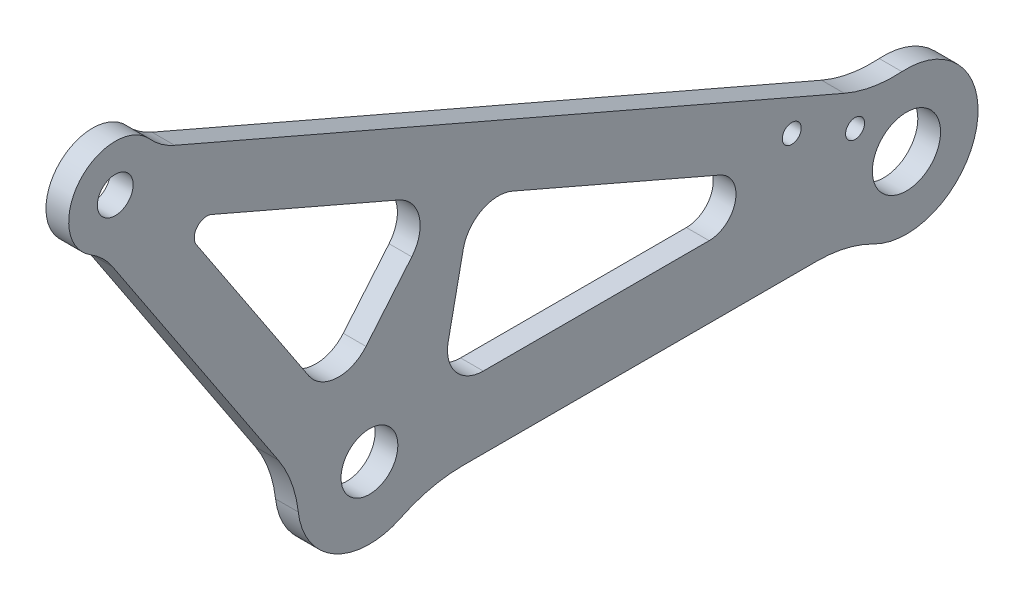
SolidWorks part; units mm, degrees
material "AISI 1020"
ref_plane "Front Plane" through (0, 0, 0) normal (0, 0, 1) x (1, 0, 0)
ref_plane "Top Plane" through (0, 0, 0) normal (0, 1, 0) x (1, 0, 0)
ref_plane "Right Plane" through (0, 0, 0) normal (1, 0, 0) x (0, 0, -1)
sketch "Sketch1" plane through (0, 0, 0) normal (1, 0, 0) x (0, 0, -1)
  line L0 (-60.7171, 0) -> (60.7171, 0)
  line L3 (0, -143.7223) -> (0, 143.7223) construction
  line L4 (-149.7529, 101.5535) -> (-94.5581, 18.1812)
  line L5 (-134.4049, 119.8783) -> (67.4524, 32.5212)
  line L6 (-75, 14) -> (75, 14) construction
  line L8 (-146, 114) -> (-75, 14) construction
  arc A20 (-134.4049, 119.8783) -> (-149.7529, 101.5535) centre (-146, 114) ccw
  arc A22 (-94.5581, 18.1812) -> (-60.7171, 0) centre (-75, 14) ccw
  arc A23 (60.7171, 0) -> (67.4524, 32.5212) centre (75, 14) ccw
  point P5 (0, 0)
  point P14 (0, 0)
  dimension "D3" = 20
  dimension "D5" = 13
  dimension "D6" = 20
  dimension "D4" = 127
  dimension "D7" = 254
  dimension "D10" = 6
  dimension "D11" = 6
  dimension "D9" = 3
  dimension "D12" = 3
  dimension "D13" = 6
  dimension "D14" = 6
  dimension "D2" = 150
  dimension "D8" = 122.6418
extrude "Boss-Extrude1" add sketch "Sketch1" along normal blind 6.35
hole_wizard "3/4 (0.75) Diameter Hole1" positions "Sketch4" profile "Sketch3" hole size "3/4" standard "ANSI Inch" end condition up to next
sketch "Sketch4" plane through (6.35, 0, 0) normal (1, 0, 0) x (0, 0, -1)
  point P5 (75, 14)
sketch "Sketch3" plane through (6.35, 14, -75) normal (0, 1, 0) x (0, 0, -1)
  line L0 (0, 0) -> (0, 6.35)
  line L1 (0, 6.35) -> (9.525, 6.35)
  line L2 (9.525, 6.35) -> (9.525, 0)
  line L5 (9.525, 0) -> (0, 0)
  line L11 (0, -6.35) -> (0, 107.95) construction
  dimension "Thru Hole Dia." = 19.05
  dimension "Thru Hole Depth" = 6.35
hole_wizard "Ø10.0 (10) Diameter Hole1" positions "Sketch9" profile "Sketch6" hole size "Ø10.0" standard "ANSI Metric" end condition up to next
sketch "Sketch9" plane through (6.35, 0, 0) normal (1, 0, 0) x (0, 0, -1)
  point P0 (-146, 114)
sketch "Sketch6" plane through (6.35, 114, 146) normal (0, 1, 0) x (0, 0, -1)
  line L0 (0, 0) -> (0, 6.35)
  line L1 (0, 6.35) -> (5, 6.35)
  line L2 (5, 6.35) -> (5, 0)
  line L5 (5, 0) -> (0, 0)
  line L11 (0, -6.35) -> (0, 107.95) construction
  dimension "Thru Hole Dia." = 10
  dimension "Thru Hole Depth" = 6.35
hole_wizard "Ø5/8\" Diameter Hole2" positions "Sketch16" profile "Sketch11" hole size "5/8" standard "ANSI Inch" end condition up to next
sketch "Sketch16" plane through (6.35, 0, 0) normal (1, 0, 0) x (0, 0, -1)
  line L0 (75, 14) -> (157.5513, 156.983)
  line L2 (0, 0) -> (0, 108.153) construction
  line L4 (-146, 114) -> (-119.4521, 194.8786)
  line L6 (-174.545, 70.324) -> (-178.0536, 59.6351) construction
  line L7 (-174.545, 70.324) -> (-178.0536, 59.6351) construction
  arc A0 (-94.5581, 18.1812) -> (-60.7171, 0) centre (-75, 14) ccw construction
  point P0 (-75, 14)
  dimension "D1" = 30
sketch "Sketch11" plane through (6.35, 14, 75) normal (0, 1, 0) x (0, 0, -1)
  line L0 (0, 0) -> (0, 6.35)
  line L1 (0, 6.35) -> (7.9375, 6.35)
  line L2 (7.9375, 6.35) -> (7.9375, 0)
  line L5 (7.9375, 0) -> (0, 0)
  line L11 (0, -6.35) -> (0, 107.95) construction
  dimension "Thru Hole Dia." = 15.875
  dimension "Thru Hole Depth" = 6.35
sketch "Sketch8" plane through (6.35, 0, 0) normal (1, 0, 0) x (0, 0, -1)
  line L2 (-54.5605, 67.8903) -> (-46.3008, 64.3157) construction
  line L3 (-52.9877, 32.028) -> (-48.7918, 52.2877)
  line L7 (-75.9573, 42.3434) -> (-63.1664, 57.6152)
  line L9 (-123.3455, 90.6494) -> (-91.9619, 43.2441)
  line L10 (-119.037, 95.7935) -> (-66.861, 73.2135)
  line L11 (19.8861, 20) -> (-43.1955, 20)
  line L12 (67.4524, 32.5212) -> (-134.4049, 119.8783) construction
  line L13 (-149.7529, 101.5535) -> (-94.5581, 18.1812) construction
  line L14 (-60.7171, 0) -> (60.7171, 0) construction
  line L15 (-84.5632, 32.0683) -> (-84.2827, 31.6447) construction
  line L16 (-55.4787, 20) -> (-55.9867, 20) construction
  line L17 (-54.5605, 67.8903) -> (-46.3008, 64.3157) construction
  line L18 (-35.0279, 59.4372) -> (22.8649, 34.3831)
  line L19 (-120.4271, 92.5814) -> (-104.3957, 79.1543) construction
  line L20 (19.8861, 27.5) -> (27.9693, 25.826) construction
  line L21 (-29.8567, 10) -> (10.3311, 10) construction
  arc A0 (-52.9877, 32.028) -> (-43.1955, 20) centre (-43.1955, 30) ccw
  arc A2 (-48.7918, 52.2877) -> (-35.0279, 59.4372) centre (-38.9996, 50.2597) cw
  arc A4 (-63.1664, 57.6152) -> (-66.861, 73.2135) centre (-70.8327, 64.0361) ccw
  arc A14 (-119.037, 95.7935) -> (-123.3455, 90.6494) centre (-120.4271, 92.5814) ccw
  arc A20 (-75.9573, 42.3434) -> (-91.9619, 43.2441) centre (-83.6236, 48.7643) cw
  arc A25 (-134.4049, 119.8783) -> (-149.7529, 101.5535) centre (-146, 114) ccw construction
  circle A27 centre (-146, 114) radius 5 construction
  arc A36 (-94.5581, 18.1812) -> (-60.7171, 0) centre (-75, 14) ccw construction
  circle A39 centre (-75, 14) radius 7.9375 construction
  arc A40 (19.8861, 20) -> (22.8649, 34.3831) centre (19.8861, 27.5) ccw
  circle A54 centre (-75, 14) radius 19.9375
  arc A55 (-55.9867, 20) -> (-84.2827, 31.6447) centre (-75, 14) ccw construction
  point P7 (-33.5049, 66.1162)
  point P19 (-33.4763, 76.1997)
  dimension "D8" = 8
  dimension "D9" = 12.0625
  dimension "D11" = 9
  dimension "D7" = 4
  dimension "D1" = 7
  dimension "D10" = 24.8576
  dimension "D2" = 15
  dimension "D12" = 10
  dimension "D13" = 14.6862
  dimension "D3" = 12
  dimension "D5" = 16
  dimension "D6" = 20
  dimension "D4" = 16
extrude "Cut-Extrude1" cut sketch "Sketch8" against normal up to next
fillet "Fillet1" radius 35 1 edges at (3.175, 18.1812, 94.5581)
fillet "Fillet3" radius 35 2 edges at (3.175, 32.5212, -67.4524) (3.175, 0, -60.7171)
fillet "Fillet4" radius 20 2 edges at (3.175, 101.5535, 149.7529) (3.175, 119.8783, 134.4049)
fillet "Fillet6" radius 40 1 edges at (3.175, 0, 60.7171)
sketch "Sketch17" [suppressed] plane through (0, 0, 0) normal (-1, 0, 0) x (0, 0, 1)
  line L0 (-31.692, 47.9971) -> (-74.6306, 61.6169)
  line L1 (-57.6351, 36.7697) -> (129.4114, 117.7173) construction
  line L2 (-134.8033, 70.2122) -> (-137.856, 60.5882)
  line L3 (-135.7084, 50.8215) -> (-89.7688, 0.5136)
  line L4 (-57.6351, 36.7697) -> (-31.692, 47.9971)
  line L6 (-84.0792, 16.8799) -> (-65.9208, 11.1201) construction
  line L7 (-100.5678, 75.614) -> (-71.9719, 66.5436) construction
  line L8 (-77.8799, 4.9208) -> (-72.1201, 23.0792) construction
  line L9 (-74.6306, 61.6169) -> (-101.2349, 70.0556) construction
  line L10 (-101.2349, 70.0556) -> (-122.2479, 76.7207)
  arc A0 (-73.7404, 33.9603) -> (-65.9164, -3.8182) centre (-75, 14) ccw construction
  arc A1 (-73.7404, 33.9603) -> (-57.6351, 36.7697) centre (-71.5361, 68.8908) ccw construction
  arc A2 (-73.7404, 33.9603) -> (-89.7688, 0.5136) centre (-75, 14) ccw
  arc A3 (-73.7404, 33.9603) -> (-57.6351, 36.7697) centre (-71.5361, 68.8908) ccw
  arc A4 (-137.856, 60.5882) -> (-135.7084, 50.8215) centre (-128.324, 57.5647) ccw
  arc A5 (-122.2479, 76.7207) -> (-134.8033, 70.2122) centre (-125.2713, 67.1887) ccw
  arc A6 (-101.2349, 70.0556) -> (-74.6306, 61.6169) centre (-86.2698, 71.0788) ccw
  circle A7 centre (-75, 14) radius 9.525 construction
  arc A8 (-71.9719, 66.5436) -> (-100.5678, 75.614) centre (-86.2698, 71.0788) ccw construction
  arc A9 (-100.5678, 75.614) -> (-101.2349, 70.0556) centre (-86.2698, 71.0788) ccw construction
  arc A10 (-74.6306, 61.6169) -> (-71.9719, 66.5436) centre (-86.2698, 71.0788) ccw construction
  point P15 (-75, 14)
  point P18 (-86.2698, 71.0788)
  point P26 (-139.6016, 55.0849)
  point P29 (-131.7798, 79.7442)
  point P31 (-75, 14)
  dimension "D5" = 10
  dimension "D1" = 41
  dimension "D2" = 45.5
  dimension "D3" = 120
  dimension "D4" = 74
  dimension "D6" = 30
  dimension "D7" = 51
  dimension "D8" = 28
extrude "Boss-Extrude2" [suppressed] add sketch "Sketch17" against normal up to surface (6.35 mm away)
hole_wizard "M5 Clearance Hole1" positions "Sketch21" profile "Sketch19" hole size "M5" standard "ANSI Metric"
sketch "Sketch21" [suppressed] plane through (0, 0, 0) normal (-1, 0, 0) x (0, 0, 1)
  line L0 (-125.2509, 66.6577) -> (-73.9498, 50.3854) construction
  line L2 (-31.692, 47.9971) -> (-74.6306, 61.6169) construction
  line L3 (-75, 14) -> (-64.4178, 47.3619) construction
  line L5 (-134.8033, 70.2122) -> (-137.856, 60.5882) construction
  point P1 (-125.2509, 66.6577)
  point P3 (-73.9498, 50.3854)
  dimension "D1" = 35
  dimension "D2" = 10
  dimension "D3" = 53.82
sketch "Sketch19" plane through (0, 66.6577, -125.2509) normal (0, 1, 0) x (0, 0, 1)
  line L0 (0, 0) -> (0, 6.35)
  line L1 (0, 6.35) -> (2.65, 6.35)
  line L2 (2.65, 6.35) -> (2.65, 0)
  line L5 (2.65, 0) -> (0, 0)
  line L11 (0, -6.35) -> (0, 107.95) construction
  dimension "Thru Hole Dia." = 5.3
  dimension "Thru Hole Depth" = 6.35
fillet "Fillet7" [suppressed] radius 25
fillet "Fillet8" [suppressed] radius 5
sketch "Sketch22" plane through (6.35, 0, 0) normal (1, 0, 0) x (0, 0, -1)
  line L0 (-4.9301, 63.8459) -> (-11.2849, 49.162) construction
  line L1 (57.6351, 36.7697) -> (-129.4114, 117.7173) construction
  line L2 (22.8649, 34.3831) -> (-35.0279, 59.4372) construction
  line L3 (-8.1075, 56.5039) -> (70.5938, 22.4446) construction
  line L4 (70.5938, 22.4446) -> (60.6448, 26.7502) construction
  circle A0 centre (75, 14) radius 9.525 construction
  circle A1 centre (60.6448, 26.7502) radius 2.65
  dimension "D2" = 5.3
  dimension "D1" = 10.8408
extrude "Cut-Extrude2" cut sketch "Sketch22" against normal blind 10
sketch "Sketch24" plane through (6.35, 0, 0) normal (1, 0, 0) x (0, 0, -1)
  line L0 (12.6689, 56.2296) -> (6.3142, 41.5457) construction
  line L1 (57.6351, 36.7697) -> (-129.4114, 117.7173) construction
  line L2 (22.8649, 34.3831) -> (-35.0279, 59.4372) construction
  line L3 (9.4916, 48.8876) -> (70.5938, 22.4446) construction
  line L4 (60.6448, 26.7502) -> (42.9665, 34.4008) construction
  circle A0 centre (75, 14) radius 9.525 construction
  circle A3 centre (42.9665, 34.4008) radius 2.65
  dimension "D1" = 19.2627
  dimension "D2" = 5.3
extrude "Cut-Extrude3" cut sketch "Sketch24" against normal blind 10
equation "\"D11@Sketch1\"=\"D10@Sketch1\""
equation "\"D12@Sketch1\"=\"D9@Sketch1\""
equation "\"D14@Sketch1\"=\"D13@Sketch1\""
